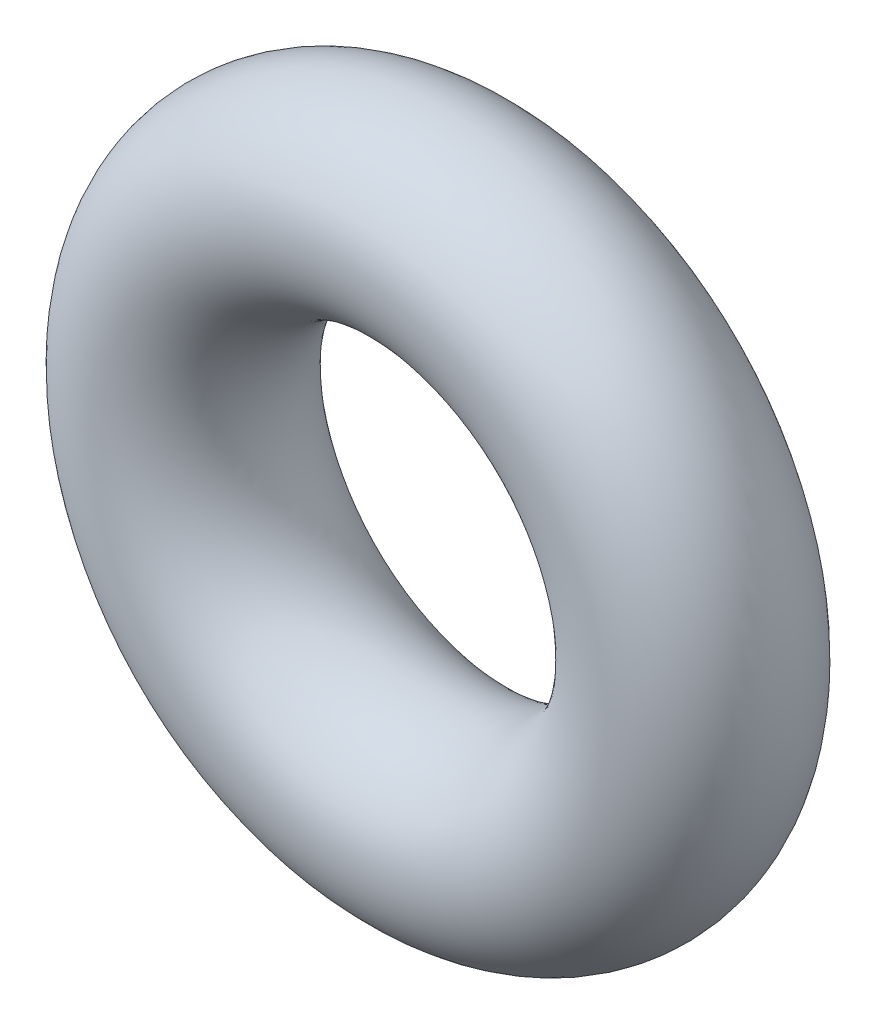
SolidWorks part; units mm, degrees
material "Rubber"
ref_plane "Front Plane" through (0, 0, 0) normal (0, 0, 1) x (1, 0, 0)
ref_plane "Top Plane" through (0, 0, 0) normal (0, 1, 0) x (1, 0, 0)
ref_plane "Right Plane" through (0, 0, 0) normal (1, 0, 0) x (0, 0, -1)
sketch "Sketch1" plane through (0, 0, 0) normal (1, 0, 0) x (0, 0, -1)
  line L0 (0, 0) -> (1.597, 0) construction
  circle A0 centre (0, 2.3368) radius 0.889
  dimension "D1" = 1.778
  dimension "D2" = 2.3368
revolve "Revolve1" add sketch "Sketch1" angle 360 about L0
sketch "Sketch2" plane through (0, 0, 0) normal (0, 0, 1) x (1, 0, 0)
  circle A0 centre (0, 0) radius 1.4478 construction
  dimension "D1" = 2.8956
equation "\"D2@Sketch1\"=0.114/2 + 0.07/2"
